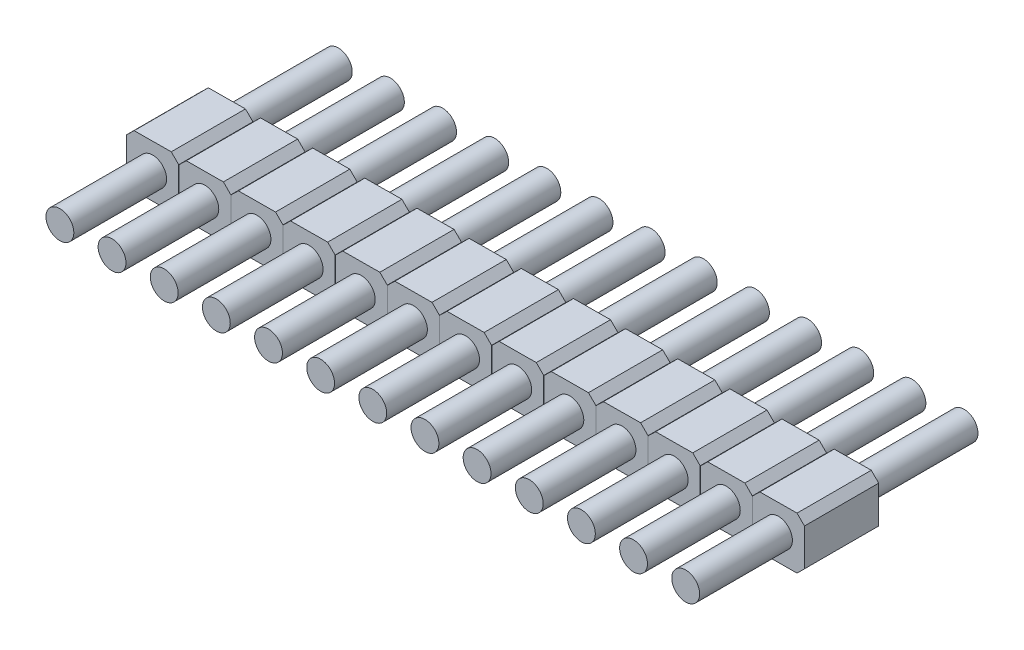
SolidWorks part; units mm, degrees
ref_plane "Front Plane" through (0, 0, 0) normal (0, 0, 1) x (1, 0, 0)
ref_plane "Top Plane" through (0, 0, 0) normal (0, 1, 0) x (1, 0, 0)
ref_plane "Right Plane" through (0, 0, 0) normal (1, 0, 0) x (0, 0, -1)
sketch "Sketch1" plane through (0, 0, 0) normal (0, 0, 1) x (1, 0, 0)
  line L55 (23.6788, 3.2645) -> (23.6788, 1.2645)
  line L70 (26.0788, 0.8645) -> (24.0788, 0.8526)
  line L71 (26.0788, 3.6665) -> (26.0788, 0.8645) construction
  line L89 (23.6788, 3.2645) -> (26.4788, 3.2645) construction
  line L91 (26.4788, 1.2645) -> (23.6788, 1.2645) construction
  line L98 (26.0788, 3.6665) -> (26.4788, 3.2645)
  line L100 (24.0788, 3.6526) -> (24.0788, 0.8526) construction
  line L111 (24.0788, 3.6526) -> (23.6788, 3.2645)
  line L112 (26.4788, 1.2645) -> (26.0788, 0.8645)
  line L113 (24.0788, 0.8526) -> (23.6788, 1.2645)
  line L114 (21.2688, 3.6526) -> (23.2688, 3.6665)
  line L115 (23.2688, 3.6665) -> (23.6688, 3.2645)
  line L116 (23.6688, 3.2645) -> (23.6688, 1.2645)
  line L117 (23.6688, 1.2645) -> (23.2688, 0.8645)
  line L118 (23.2688, 0.8645) -> (21.2688, 0.8526)
  line L119 (21.2688, 0.8526) -> (20.8688, 1.2645)
  line L120 (20.8688, 3.2645) -> (20.8688, 1.2645)
  line L121 (21.2688, 3.6526) -> (20.8688, 3.2645)
  line L122 (18.4588, 3.6526) -> (20.4588, 3.6665)
  line L123 (20.4588, 3.6665) -> (20.8588, 3.2645)
  line L124 (20.8588, 3.2645) -> (20.8588, 1.2645)
  line L125 (20.8588, 1.2645) -> (20.4588, 0.8645)
  line L126 (20.4588, 0.8645) -> (18.4588, 0.8526)
  line L127 (18.4588, 0.8526) -> (18.0588, 1.2645)
  line L128 (18.0588, 3.2645) -> (18.0588, 1.2645)
  line L129 (18.4588, 3.6526) -> (18.0588, 3.2645)
  line L130 (15.6488, 3.6526) -> (17.6488, 3.6665)
  line L131 (17.6488, 3.6665) -> (18.0488, 3.2645)
  line L132 (18.0488, 3.2645) -> (18.0488, 1.2645)
  line L133 (18.0488, 1.2645) -> (17.6488, 0.8645)
  line L134 (17.6488, 0.8645) -> (15.6488, 0.8526)
  line L135 (15.6488, 0.8526) -> (15.2488, 1.2645)
  line L136 (15.2488, 3.2645) -> (15.2488, 1.2645)
  line L137 (15.6488, 3.6526) -> (15.2488, 3.2645)
  line L138 (12.8388, 3.6526) -> (14.8388, 3.6665)
  line L139 (14.8388, 3.6665) -> (15.2388, 3.2645)
  line L140 (15.2388, 3.2645) -> (15.2388, 1.2645)
  line L141 (15.2388, 1.2645) -> (14.8388, 0.8645)
  line L142 (14.8388, 0.8645) -> (12.8388, 0.8526)
  line L143 (12.8388, 0.8526) -> (12.4388, 1.2645)
  line L144 (12.4388, 3.2645) -> (12.4388, 1.2645)
  line L145 (12.8388, 3.6526) -> (12.4388, 3.2645)
  line L146 (10.0288, 3.6526) -> (12.0288, 3.6665)
  line L148 (12.0288, 3.6665) -> (12.4288, 3.2645)
  line L149 (12.4288, 3.2645) -> (12.4288, 1.2645)
  line L150 (12.4288, 1.2645) -> (12.0288, 0.8645)
  line L151 (12.0288, 0.8645) -> (10.0288, 0.8526)
  line L152 (10.0288, 0.8526) -> (9.6288, 1.2645)
  line L154 (9.6288, 3.2645) -> (9.6288, 1.2645)
  line L156 (10.0288, 3.6526) -> (9.6288, 3.2645)
  line L157 (7.2188, 3.6526) -> (9.2188, 3.6665)
  line L158 (9.2188, 3.6665) -> (9.6188, 3.2645)
  line L159 (9.6188, 3.2645) -> (9.6188, 1.2645)
  line L160 (9.6188, 1.2645) -> (9.2188, 0.8645)
  line L162 (9.2188, 0.8645) -> (7.2188, 0.8526)
  line L164 (7.2188, 0.8526) -> (6.8188, 1.2645)
  line L165 (6.8188, 3.2645) -> (6.8188, 1.2645)
  line L166 (7.2188, 3.6526) -> (6.8188, 3.2645)
  line L167 (4.4088, 3.6526) -> (6.4088, 3.6665)
  line L168 (6.4088, 3.6665) -> (6.8088, 3.2645)
  line L170 (6.8088, 3.2645) -> (6.8088, 1.2645)
  line L171 (6.8088, 1.2645) -> (6.4088, 0.8645)
  line L172 (6.4088, 0.8645) -> (4.4088, 0.8526)
  line L173 (4.4088, 0.8526) -> (4.0088, 1.2645)
  line L174 (4.0088, 3.2645) -> (4.0088, 1.2645)
  line L175 (4.4088, 3.6526) -> (4.0088, 3.2645)
  line L176 (1.5988, 3.6526) -> (3.5988, 3.6665)
  line L177 (3.5988, 3.6665) -> (3.9988, 3.2645)
  line L178 (3.9988, 3.2645) -> (3.9988, 1.2645)
  line L179 (3.9988, 1.2645) -> (3.5988, 0.8645)
  line L180 (3.5988, 0.8645) -> (1.5988, 0.8526)
  line L181 (1.5988, 0.8526) -> (1.1988, 1.2645)
  line L182 (1.1988, 3.2645) -> (1.1988, 1.2645)
  line L183 (1.5988, 3.6526) -> (1.1988, 3.2645)
  line L184 (-1.2112, 3.6526) -> (0.7888, 3.6665)
  line L185 (0.7888, 3.6665) -> (1.1888, 3.2645)
  line L186 (1.1888, 3.2645) -> (1.1888, 1.2645)
  line L188 (1.1888, 1.2645) -> (0.7888, 0.8645)
  line L189 (0.7888, 0.8645) -> (-1.2112, 0.8526)
  line L190 (-1.2112, 0.8526) -> (-1.6112, 1.2645)
  line L191 (24.0788, 3.6526) -> (26.0788, 3.6665)
  line L195 (26.4788, 3.2645) -> (26.4788, 1.2645)
  line L203 (-1.6112, 3.2645) -> (-1.6112, 1.2645)
  line L210 (-1.2112, 3.6526) -> (-1.6112, 3.2645)
  line L215 (-4.0212, 3.6526) -> (-2.0212, 3.6665)
  line L232 (-2.0212, 3.6665) -> (-1.6212, 3.2645)
  line L233 (-1.6212, 3.2645) -> (-1.6212, 1.2645)
  line L241 (-1.6212, 1.2645) -> (-2.0212, 0.8645)
  line L243 (-2.0212, 0.8645) -> (-4.0212, 0.8526)
  line L261 (-4.0212, 0.8526) -> (-4.4212, 1.2645)
  line L263 (-4.4212, 3.2645) -> (-4.4212, 1.2645)
  line L266 (-4.0212, 3.6526) -> (-4.4212, 3.2645)
  line L267 (-6.8312, 3.6526) -> (-4.8312, 3.6665)
  line L268 (-4.8312, 3.6665) -> (-4.4312, 3.2645)
  line L269 (-4.4312, 3.2645) -> (-4.4312, 1.2645)
  line L270 (-4.4312, 1.2645) -> (-4.8312, 0.8645)
  line L271 (-4.8312, 0.8645) -> (-6.8312, 0.8526)
  line L272 (-6.8312, 0.8526) -> (-7.2312, 1.2645)
  line L273 (-7.2312, 3.2645) -> (-7.2312, 1.2645)
  line L274 (-6.8312, 3.6526) -> (-7.2312, 3.2645)
  line L275 (-9.6412, 3.6526) -> (-7.6412, 3.6665)
  line L276 (-7.6412, 3.6665) -> (-7.2412, 3.2645)
  line L277 (-7.2412, 3.2645) -> (-7.2412, 1.2645)
  line L278 (-7.2412, 1.2645) -> (-7.6412, 0.8645)
  line L279 (-7.6412, 0.8645) -> (-9.6412, 0.8526)
  line L280 (-9.6412, 0.8526) -> (-10.0412, 1.2645)
  line L281 (-10.0412, 3.2645) -> (-10.0412, 1.2645)
  line L282 (-9.6412, 3.6526) -> (-10.0412, 3.2645)
  dimension "D1" = 13
  dimension "D2" = 2.8
  dimension "D3" = 2.8
extrude "Boss-Extrude1" add sketch "Sketch1" along normal blind 4
sketch "Sketch3" plane through (0, 0, 4) normal (0, 0, 1) x (1, 0, 0)
  line L0 (-9.6412, 3.6526) -> (-7.6412, 3.6665) construction
  line L1 (-7.2412, 3.2645) -> (-7.2412, 1.2645) construction
  circle A0 centre (-8.6412, 2.2645) radius 0.75
  circle A1 centre (-5.8312, 2.2645) radius 0.75
  circle A2 centre (-3.0212, 2.2645) radius 0.75
  circle A3 centre (-0.2112, 2.2645) radius 0.75
  circle A4 centre (2.5988, 2.2645) radius 0.75
  circle A5 centre (5.4088, 2.2645) radius 0.75
  circle A6 centre (8.2188, 2.2645) radius 0.75
  circle A7 centre (11.0288, 2.2645) radius 0.75
  circle A8 centre (13.8388, 2.2645) radius 0.75
  circle A9 centre (16.6488, 2.2645) radius 0.75
  circle A10 centre (19.4588, 2.2645) radius 0.75
  circle A11 centre (22.2688, 2.2645) radius 0.75
  circle A12 centre (25.0788, 2.2645) radius 0.75
  point P0 (-8.6412, 3.6595)
  point P1 (-7.2412, 2.2645)
  point P4 (-8.6412, 2.2645)
  dimension "D1" = 1.5
  dimension "D2" = 13
extrude "Boss-Extrude3" add sketch "Sketch3" along normal blind 5 and the other way blind 10
